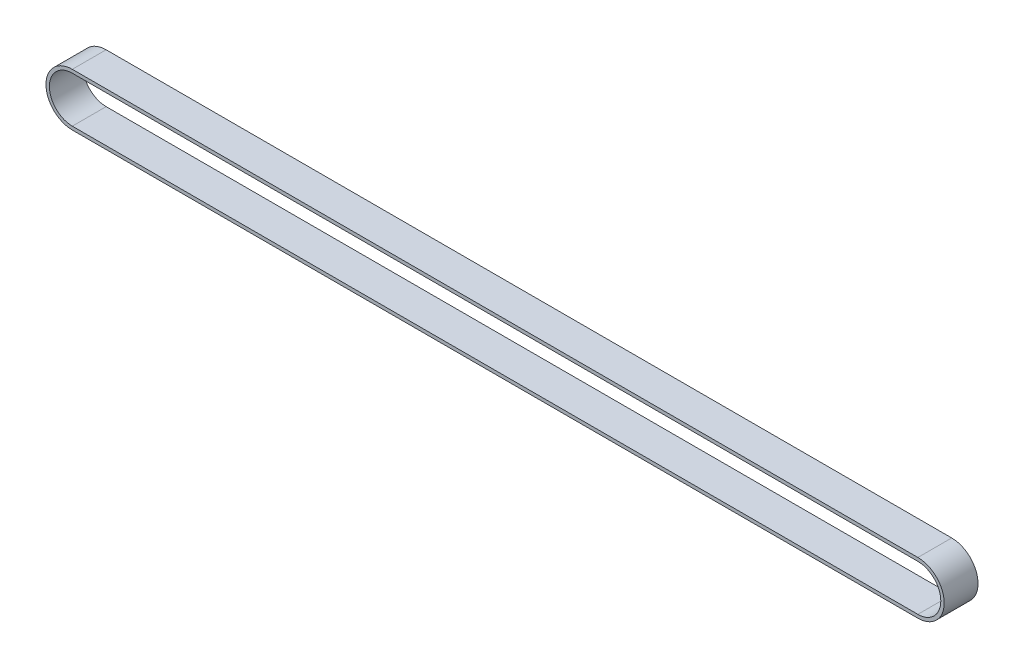
SolidWorks part; units mm, degrees
ref_plane "前视基准面" through (0, 0, 0) normal (0, 0, 1) x (1, 0, 0)
ref_plane "上视基准面" through (0, 0, 0) normal (0, 1, 0) x (1, 0, 0)
ref_plane "右视基准面" through (0, 0, 0) normal (1, 0, 0) x (0, 0, -1)
sketch "草图1" plane through (0, 0, 0) normal (0, 0, 1) x (1, 0, 0)
  line L0 (125, 0) -> (-125, 0) construction
  line L1 (125, -6.78) -> (-125, -6.78)
  line L2 (125, 6.78) -> (-125, 6.78)
  line L3 (125, -7.78) -> (-125, -7.78)
  line L4 (125, 7.78) -> (-125, 7.78)
  arc A0 (125, -6.78) -> (125, 6.78) centre (125, 0) ccw
  arc A1 (-125, 6.78) -> (-125, -6.78) centre (-125, 0) ccw
  arc A2 (-125, 7.78) -> (-125, -7.78) centre (-125, 0) ccw
  arc A3 (125, -7.78) -> (125, 7.78) centre (125, 0) ccw
  point P2 (0, 0)
  dimension "D1" = 6.78
  dimension "D2" = 250
  dimension "D3" = 1
extrude "凸台-拉伸1" add sketch "草图1" along normal mid plane 10
